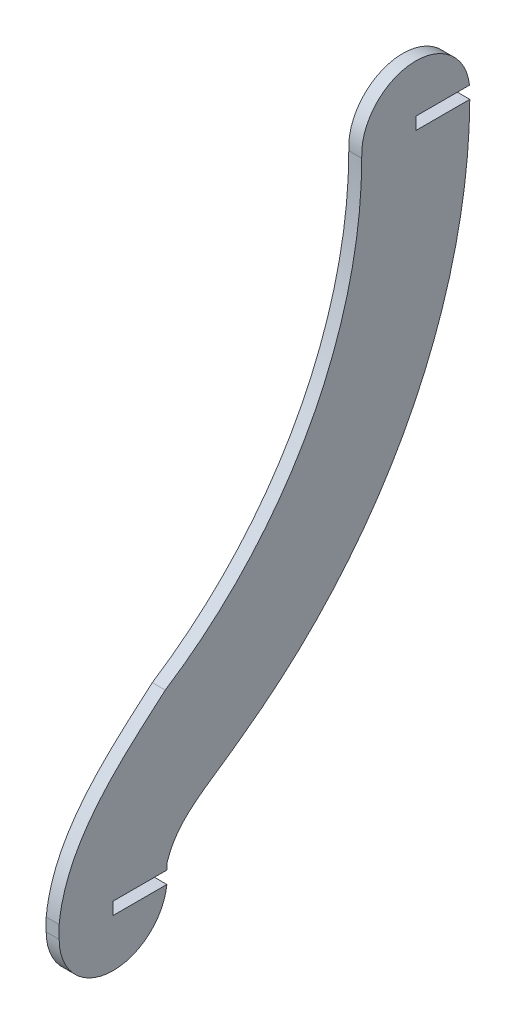
SolidWorks part; units mm, degrees
ref_plane "Front Plane" through (0, 0, 0) normal (0, 0, 1) x (1, 0, 0)
ref_plane "Top Plane" through (0, 0, 0) normal (0, 1, 0) x (1, 0, 0)
ref_plane "Right Plane" through (0, 0, 0) normal (1, 0, 0) x (0, 0, -1)
sketch "Sketch1" plane through (0, 0, 0) normal (1, 0, 0) x (0, 0, -1)
  line L0 (54.5436, -83.8153) -> (30, -118.5) construction
  line L5 (-125, 1.5) -> (125, 1.5) construction
  line L6 (-125, 1.5) -> (-125, -1.5) construction
  line L7 (-125, -1.5) -> (125, -1.5) construction
  line L8 (125, 1.5) -> (125, -1.5) construction
  line L9 (-125, 1.5) -> (125, -1.5) construction
  line L10 (-125, -1.5) -> (125, 1.5) construction
  line L11 (-55, -121.5) -> (55, -121.5) construction
  line L12 (-55, -121.5) -> (-55, -118.5) construction
  line L13 (-55, -118.5) -> (55, -118.5) construction
  line L14 (55, -121.5) -> (55, -118.5) construction
  line L15 (-55, -121.5) -> (55, -118.5) construction
  line L16 (-55, -118.5) -> (55, -121.5) construction
  line L17 (72.3473, -101.9356) -> (50.4075, -132.9407) construction
  line L18 (125, 0) -> (125, 1.5)
  line L19 (55, -118.5) -> (55, -121.5)
  line L20 (30, -118.5) -> (30, -121.5)
  circle A0 centre (0, 0) radius 100 construction
  arc A1 (100, 0) -> (54.5436, -83.8153) centre (0, 0) cw
  arc A3 (125, 0) -> (72.3473, -101.9356) centre (0, 0) cw
  arc A5 (100, 0) -> (125, 1.5) centre (112.5, 0.75) cw
  arc A6 (55, -121.5) -> (30, -121.5) centre (42.5, -121.5) cw
  spline S0 degree 3 poles (54.5436, -83.8153) (44.4344, -92.6089) (31.5813, -102.9457) (30, -118.5) knots 0 0 0 0 1 1 1 1
  spline S1 degree 3 poles (55, -118.5) (57.3843, -110.8686) (64.5489, -107.8606) (72.3473, -101.9356) knots 0 0 0 0 1 1 1 1
  point P7 (0, -120)
  point P21 (0, 0)
  dimension "D1" = 200
  dimension "D8" = 25
  dimension "D4" = 3
  dimension "D5" = 110
  dimension "D6" = 120
  dimension "D7" = 25
extrude "Boss-Extrude2" add sketch "Sketch1" along normal blind 3
sketch "Sketch2" plane through (3, 0, 0) normal (1, 0, 0) x (0, 0, -1)
  line L1 (125, -0.685) -> (112.5, -0.685)
  line L2 (125, -0.685) -> (125, 2.185)
  line L3 (125, 2.185) -> (112.5, 2.185)
  line L4 (112.5, -0.685) -> (112.5, 2.185)
  line L6 (55, -120.065) -> (42.5, -120.065)
  line L7 (55, -120.065) -> (55, -122.935)
  line L8 (55, -122.935) -> (42.5, -122.935)
  line L9 (42.5, -120.065) -> (42.5, -122.935)
  arc A1 (30, -121.5) -> (55, -121.5) centre (42.5, -121.5) ccw construction
  arc A2 (125, 1.5) -> (100, 0) centre (112.5, 0.75) ccw construction
  point P9 (42.5, -121.5)
  point P13 (42.5, -134)
  point P14 (112.5, 0.75)
  point P18 (111.75, 13.25)
  dimension "D1" = 12.5
  dimension "D2" = 2.87
  dimension "D3" = 12.5
  dimension "D4" = 2.87
  dimension "D5" = 12.5
  dimension "D6" = 12.5
extrude "Cut-Extrude1" cut sketch "Sketch2" against normal blind 3
